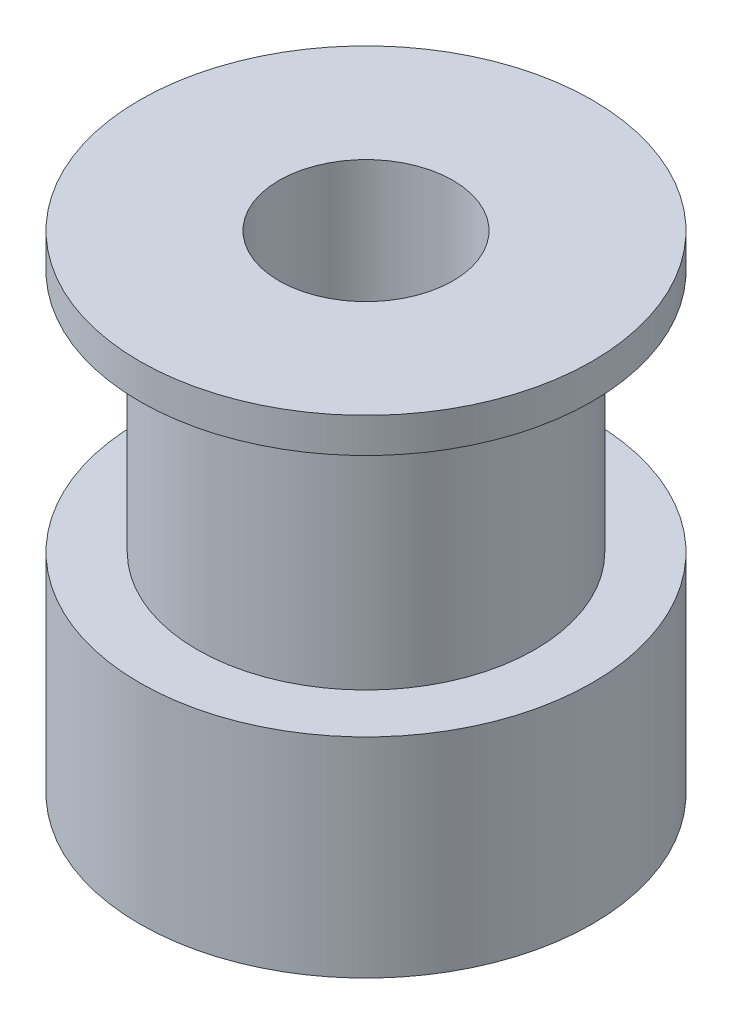
SolidWorks part; units mm, degrees
ref_plane "前视基准面" through (0, 0, 0) normal (0, 0, 1) x (1, 0, 0)
ref_plane "上视基准面" through (0, 0, 0) normal (0, 1, 0) x (1, 0, 0)
ref_plane "右视基准面" through (0, 0, 0) normal (1, 0, 0) x (0, 0, -1)
other "Configuration Table"
sketch "草图1" plane through (0, 0, 0) normal (0, 1, 0) x (1, 0, 0)
  circle A0 centre (0, 0) radius 6.5
  dimension "D1" = 13
extrude "凸台-拉伸1" add sketch "草图1" along normal blind 6
sketch "草图2" plane through (0, 6, 0) normal (0, 1, 0) x (1, 0, 0)
  circle A0 centre (0, 0) radius 4.85
  dimension "D1" = 9.7
extrude "凸台-拉伸2" add sketch "草图2" along normal blind 7
sketch "草图3" plane through (0, 13, 0) normal (0, 1, 0) x (1, 0, 0)
  circle A0 centre (0, 0) radius 6.5 construction
  circle A1 centre (0, 0) radius 6.5
extrude "凸台-拉伸3" add sketch "草图3" along normal blind 1
sketch "草图4" plane through (0, 14, 0) normal (0, 1, 0) x (1, 0, 0)
  circle A0 centre (0, 0) radius 2.5
  dimension "D1" = 5
extrude "切除-拉伸1" cut sketch "草图4" against normal up to next
